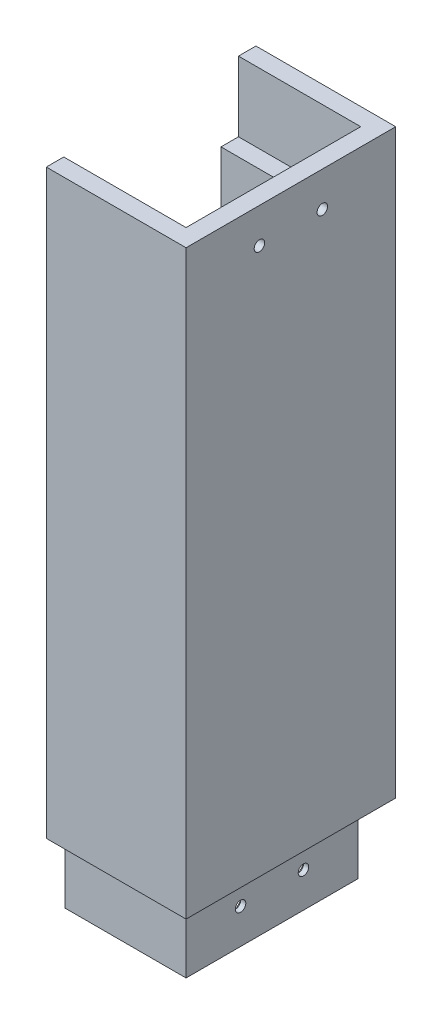
SolidWorks part; units mm, degrees
ref_plane "Front Plane" through (0, 0, 0) normal (0, 0, 1) x (1, 0, 0)
ref_plane "Top Plane" through (0, 0, 0) normal (0, 1, 0) x (1, 0, 0)
ref_plane "Right Plane" through (0, 0, 0) normal (1, 0, 0) x (0, 0, -1)
sketch "Sketch3" plane through (0, 0, 0) normal (0, 1, 0) x (1, 0, 0)
  line L1 (0, -17.4625) -> (0, 17.4625) construction
  line L3 (0, 16.625) -> (-25.4, 16.625)
  line L4 (-25.4, 16.625) -> (-25.4, 10.275)
  line L5 (-25.4, 10.275) -> (-6.985, 10.275)
  line L6 (-6.35, 9.64) -> (-6.35, -14.49)
  line L7 (0, -21.475) -> (-25.4, -21.475)
  line L8 (-25.4, -21.475) -> (-25.4, -15.125)
  line L9 (-25.4, -15.125) -> (-6.985, -15.125)
  line L10 (0, 16.625) -> (0, -21.475)
  arc A0 (-6.35, 9.64) -> (-6.985, 10.275) centre (-6.985, 9.64) ccw
  arc A1 (-6.35, -14.49) -> (-6.985, -15.125) centre (-6.985, -14.49) cw
  point P14 (-6.35, 10.275)
  point P17 (-6.35, -15.125)
  dimension "D7" = 0.635
  dimension "D1" = 6.35
  dimension "D2" = 6.35
  dimension "D3" = 19.05
  dimension "D4" = 6.35
  dimension "D5" = 19.05
  dimension "D6" = 25.4
sketch "Sketch4" plane through (0, 0, 0) normal (0, 0, 1) x (1, 0, 0)
  line L8 (0, 0) -> (0, -92.964)
  dimension "D1" = 92.964
sweep "Sweep1" add profiles "Sketch3" path "Sketch4"
sketch "Sketch5" plane through (0, -92.964, 0) normal (0, -1, 0) x (1, 0, 0)
  line L0 (-25.4, 18.046) -> (-3.429, 18.046)
  line L1 (-25.4, 21.475) -> (-25.4, 15.125) construction
  line L2 (-3.429, 18.046) -> (-3.429, -13.196)
  line L3 (-3.429, -13.196) -> (-25.4, -13.196)
  line L4 (-25.4, -16.625) -> (-25.4, -10.275) construction
  line L5 (-25.4, -13.196) -> (-25.4, -10.275)
  line L6 (-25.4, -10.275) -> (-6.985, -10.275)
  line L7 (-25.4, 18.046) -> (-25.4, 15.125)
  line L8 (-25.4, 15.125) -> (-6.985, 15.125)
  line L9 (-6.35, 14.49) -> (-6.35, -9.64)
  arc A0 (-6.985, 15.125) -> (-6.35, 14.49) centre (-6.985, 14.49) cw
  arc A1 (-6.35, 14.49) -> (-6.985, 15.125) centre (-6.985, 14.49) ccw construction
  arc A2 (-6.985, -10.275) -> (-6.35, -9.64) centre (-6.985, -9.64) ccw
  arc A3 (-6.985, -10.275) -> (-6.35, -9.64) centre (-6.985, -9.64) ccw construction
  dimension "D1" = 2.921
  dimension "D2" = 2.921
  dimension "D3" = 2.921
extrude "Boss-Extrude1" add sketch "Sketch5" along normal blind 12.7
sketch "Sketch6" plane through (0, 0, 0) normal (0, 1, 0) x (1, 0, 0)
  line L0 (-25.4, 13.45) -> (-25.4, 16.625)
  line L1 (-25.4, 16.625) -> (-25.4, 10.275) construction
  line L2 (-25.4, 16.625) -> (0, 16.625)
  line L3 (0, 16.625) -> (0, -21.475)
  line L4 (0, -21.475) -> (-25.4, -21.475)
  line L5 (-25.4, -21.475) -> (-25.4, -18.3)
  line L6 (-25.4, -21.475) -> (-25.4, -15.125) construction
  line L7 (-25.4, -18.3) -> (-3.175, -18.3)
  line L8 (-3.175, -18.3) -> (-3.175, 13.45)
  line L9 (-3.175, 13.45) -> (-25.4, 13.45)
  dimension "D1" = 3.175
  dimension "D2" = 3.175
  dimension "D3" = 3.175
extrude "Boss-Extrude2" add sketch "Sketch6" along normal blind 12.7
sketch "Sketch7" plane through (-3.175, 0, 0) normal (-1, 0, 0) x (0, 0, 1)
  line L2 (-10.275, 0) -> (-10.275, -105.664) construction
  line L3 (15.125, 0) -> (15.125, -105.664) construction
  line L4 (-13.45, 12.7) -> (18.3, 12.7) construction
  circle A0 centre (-3.29, 6.35) radius 0.9525
  circle A1 centre (8.14, 6.35) radius 0.9525
  dimension "D3" = 1.905
  dimension "D4" = 1.905
  dimension "D1" = 6.985
  dimension "D2" = 6.985
  dimension "D5" = 6.35
  dimension "D6" = 6.35
extrude "Cut-Extrude1" cut sketch "Sketch7" against normal through all
sketch "Sketch10" plane through (-6.35, 0, 0) normal (-1, 0, 0) x (0, 0, 1)
  line L0 (14.49, -105.664) -> (-9.64, -105.664) construction
  line L1 (-10.275, 0) -> (-10.275, -105.664) construction
  line L2 (15.125, 0) -> (15.125, -105.664) construction
  circle A0 centre (-3.29, -99.314) radius 0.9525
  circle A1 centre (8.14, -99.314) radius 0.9525
  dimension "D1" = 1.905
  dimension "D2" = 1.905
  dimension "D3" = 6.35
  dimension "D4" = 6.35
  dimension "D5" = 6.985
  dimension "D6" = 6.985
extrude "Cut-Extrude2" cut sketch "Sketch10" against normal through all
hole_wizard "CSK for #6 Flat Head Machine Screw (100)2" positions "Sketch12" profile "Sketch13" countersink size "#6" standard "ANSI Inch"
sketch "Sketch12" plane through (-6.35, 0, 0) normal (-1, 0, 0) x (0, 0, 1)
  point P0 (-3.29, -99.314)
  point P3 (8.14, -99.314)
sketch "Sketch13" plane through (-6.35, -99.314, -3.29) normal (0, 1, 0) x (0, 0, 1)
  line L0 (0, 0) -> (0, 2.5634)
  line L1 (0, 2.5634) -> (2.1526, 1.27)
  line L2 (2.1526, 1.27) -> (2.1526, 1.1669)
  line L3 (2.1526, 1.1669) -> (3.5433, 0)
  line L5 (3.5433, 0) -> (0, 0)
  line L6 (-2.1526, 1.1669) -> (-3.5433, 0) construction
  line L10 (0, 2.5634) -> (-2.1526, 1.27) construction
  line L11 (0, -6.35) -> (0, 107.95) construction
  dimension "Hole Dia." = 4.3053
  dimension "Hole Depth" = 1.27
  dimension "Near C'Sink Dia." = 7.0866
  dimension "Near C'Sink Angle" = 100
  dimension "Drill Angle" = 118
